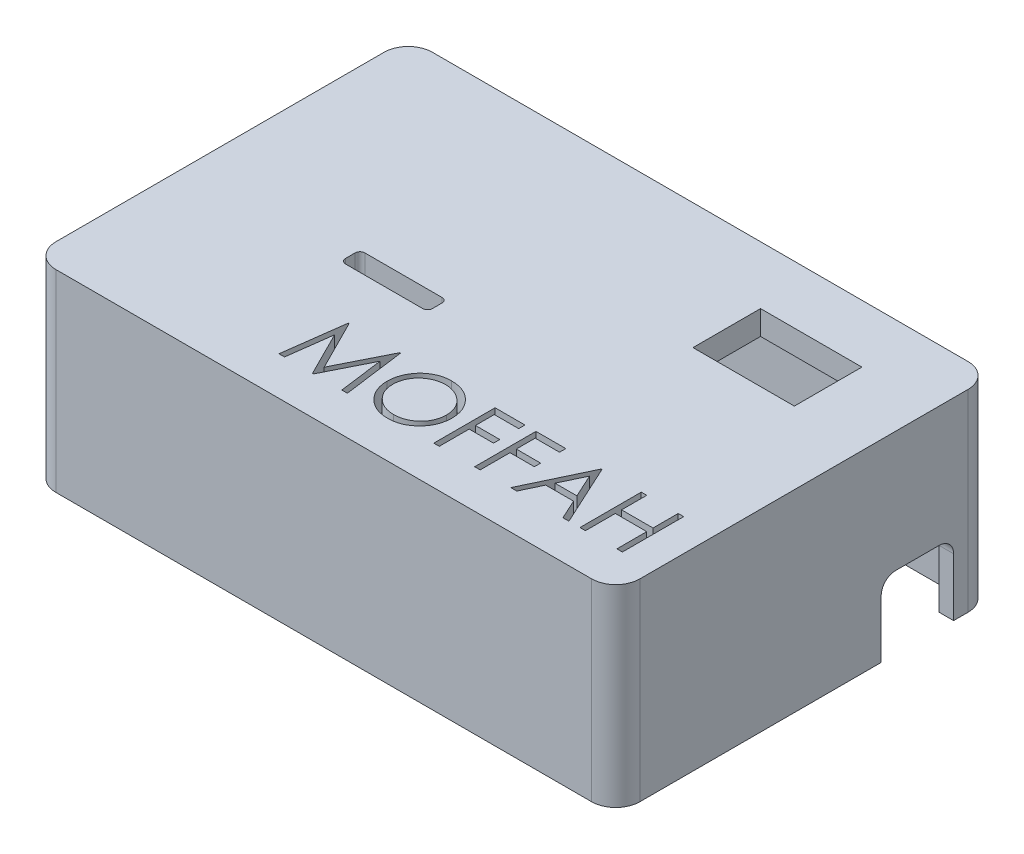
SolidWorks part; units mm, degrees
ref_plane "Alzado" through (0, 0, 0) normal (0, 0, 1) x (1, 0, 0)
ref_plane "Planta" through (0, 0, 0) normal (0, 1, 0) x (1, 0, 0)
ref_plane "Vista lateral" through (0, 0, 0) normal (1, 0, 0) x (0, 0, -1)
sketch "Croquis1" plane through (0, 0, 0) normal (0, 1, 0) x (1, 0, 0)
  line L0 (-60.5, 34) -> (-60.5, -34)
  line L1 (-55.5, 36) -> (55.5, 36)
  line L2 (-57.5, 34) -> (-57.5, -34)
  line L3 (-55.5, -36) -> (55.5, -36)
  line L4 (57.5, 34) -> (57.5, -34)
  line L5 (-55.5, -39) -> (55.5, -39)
  line L6 (60.5, 34) -> (60.5, -34)
  line L7 (-55.5, 39) -> (55.5, 39)
  arc A0 (55.5, -36) -> (57.5, -34) centre (55.5, -34) ccw
  arc A1 (55.5, 36) -> (57.5, 34) centre (55.5, 34) cw
  arc A2 (-57.5, -34) -> (-55.5, -36) centre (-55.5, -34) ccw
  arc A3 (-55.5, 36) -> (-57.5, 34) centre (-55.5, 34) ccw
  arc A4 (-60.5, -34) -> (-55.5, -39) centre (-55.5, -34) ccw
  arc A5 (55.5, -39) -> (60.5, -34) centre (55.5, -34) ccw
  arc A6 (55.5, 39) -> (60.5, 34) centre (55.5, 34) cw
  arc A7 (-55.5, 39) -> (-60.5, 34) centre (-55.5, 34) ccw
  point P4 (0, 36)
  point P6 (-57.5, 0)
  dimension "D3" = 2
  dimension "D1" = 72
  dimension "D2" = 115
  dimension "D4" = 3
extrude "Saliente-Extruir1" add sketch "Croquis1" along normal blind 35
sketch "Croquis3" plane through (0, 35, 0) normal (0, 1, 0) x (1, 0, 0)
  line L0 (55.5, 39) -> (-55.5, 39) construction
  line L1 (55.5, 39) -> (-55.5, 39)
  line L2 (-60.5, 34) -> (-60.5, -34) construction
  line L3 (-60.5, 34) -> (-60.5, -34)
  line L4 (-55.5, -39) -> (55.5, -39) construction
  line L5 (60.5, -34) -> (60.5, 34) construction
  line L6 (-55.5, -39) -> (55.5, -39)
  line L7 (60.5, -34) -> (60.5, 34)
  arc A0 (-60.5, -34) -> (-55.5, -39) centre (-55.5, -34) ccw construction
  arc A1 (60.5, 34) -> (55.5, 39) centre (55.5, 34) ccw construction
  arc A2 (-55.5, 39) -> (-60.5, 34) centre (-55.5, 34) ccw construction
  arc A3 (-60.5, -34) -> (-55.5, -39) centre (-55.5, -34) ccw
  arc A4 (60.5, 34) -> (55.5, 39) centre (55.5, 34) ccw
  arc A5 (-55.5, 39) -> (-60.5, 34) centre (-55.5, 34) ccw
  arc A6 (55.5, -39) -> (60.5, -34) centre (55.5, -34) ccw construction
  arc A7 (55.5, -39) -> (60.5, -34) centre (55.5, -34) ccw
extrude "Saliente-Extruir2" add sketch "Croquis3" along normal blind 5
sketch "Croquis5" plane through (0, 40, 0) normal (0, 1, 0) x (1, 0, 0)
  line L0 (-60.5, -31) -> (55.5, -31) construction
  line L4 (-60.5, 34) -> (-60.5, -34) construction
  line L5 (60.5, -34) -> (60.5, 34) construction
  line L6 (-60.5, 0) -> (60.5, 0) construction
  text T0 "MOFFAH\r\n" font "Century Gothic" height in points 48
  dimension "D2" = 5
  dimension "D3" = 8
extrude "Cortar-Extruir1" cut sketch "Croquis5" against normal through all both and the other way through all
sketch "Croquis6" plane through (-60.5, 0, 0) normal (-1, 0, 0) x (0, 0, 1)
  line L10 (-12.5, 0) -> (12.5, 0)
  line L11 (-12.5, 0) -> (-12.5, 5)
  line L12 (-2.5, 15) -> (2.5, 15)
  line L13 (12.5, 0) -> (12.5, 5)
  arc A2 (2.5, 15) -> (12.5, 5) centre (2.5, 5) cw
  arc A3 (-12.5, 5) -> (-2.5, 15) centre (-2.5, 5) cw
  point P4 (0, 0)
  dimension "D1" = 25
  dimension "D3" = 10
  dimension "D2" = 15
extrude "Cortar-Extruir3" cut sketch "Croquis6" against normal up to surface (3 mm away) up to face at (-57.5, 17.5, 0)
sketch "Croquis7" plane through (0, 40, 0) normal (0, 1, 0) x (1, 0, 0)
  line L0 (-60.5, 34) -> (-60.5, -34) construction
  line L1 (-26.5, -8) -> (-10.5, -8)
  line L2 (-27.5, -7) -> (-27.5, -5)
  line L3 (-26.5, -4) -> (-10.5, -4)
  line L4 (-9.5, -7) -> (-9.5, -5)
  line L6 (-55.5, -39) -> (55.5, -39) construction
  line L7 (60.5, -34) -> (60.5, 34) construction
  line L8 (24.5, 27) -> (45.5, 27)
  line L9 (24.5, 27) -> (24.5, 13)
  line L10 (24.5, 13) -> (45.5, 13)
  line L11 (45.5, 27) -> (45.5, 13)
  line L12 (55.5, 39) -> (-55.5, 39) construction
  arc A0 (-10.5, -8) -> (-9.5, -7) centre (-10.5, -7) ccw
  arc A1 (-10.5, -4) -> (-9.5, -5) centre (-10.5, -5) cw
  arc A2 (-26.5, -8) -> (-27.5, -7) centre (-26.5, -7) cw
  arc A3 (-27.5, -5) -> (-26.5, -4) centre (-26.5, -5) cw
  point P12 (-9.5, -4)
  point P17 (-27.5, -4)
  dimension "D5" = 1
  dimension "D1" = 51
  dimension "D2" = 18
  dimension "D3" = 4
  dimension "D4" = 35
  dimension "D6" = 14
  dimension "D7" = 21
  dimension "D8" = 15
  dimension "D9" = 12
extrude "Cortar-Extruir4" cut sketch "Croquis7" against normal blind 10
sketch "Croquis9" plane through (60.5, 0, 0) normal (1, 0, 0) x (0, 0, -1)
  line L0 (-34, 0) -> (34, 0) construction
  line L1 (16, 0) -> (31, 0)
  line L2 (16, 0) -> (16, 12)
  line L3 (19, 15) -> (28, 15)
  line L4 (31, 0) -> (31, 12)
  line L6 (39, 40) -> (39, 0) construction
  arc A0 (28, 15) -> (31, 12) centre (28, 12) cw
  arc A1 (16, 12) -> (19, 15) centre (19, 12) cw
  point P10 (31, 15)
  dimension "D4" = 3
  dimension "D1" = 15
  dimension "D2" = 8
  dimension "D3" = 15
extrude "Cortar-Extruir5" cut sketch "Croquis9" against normal blind 10
